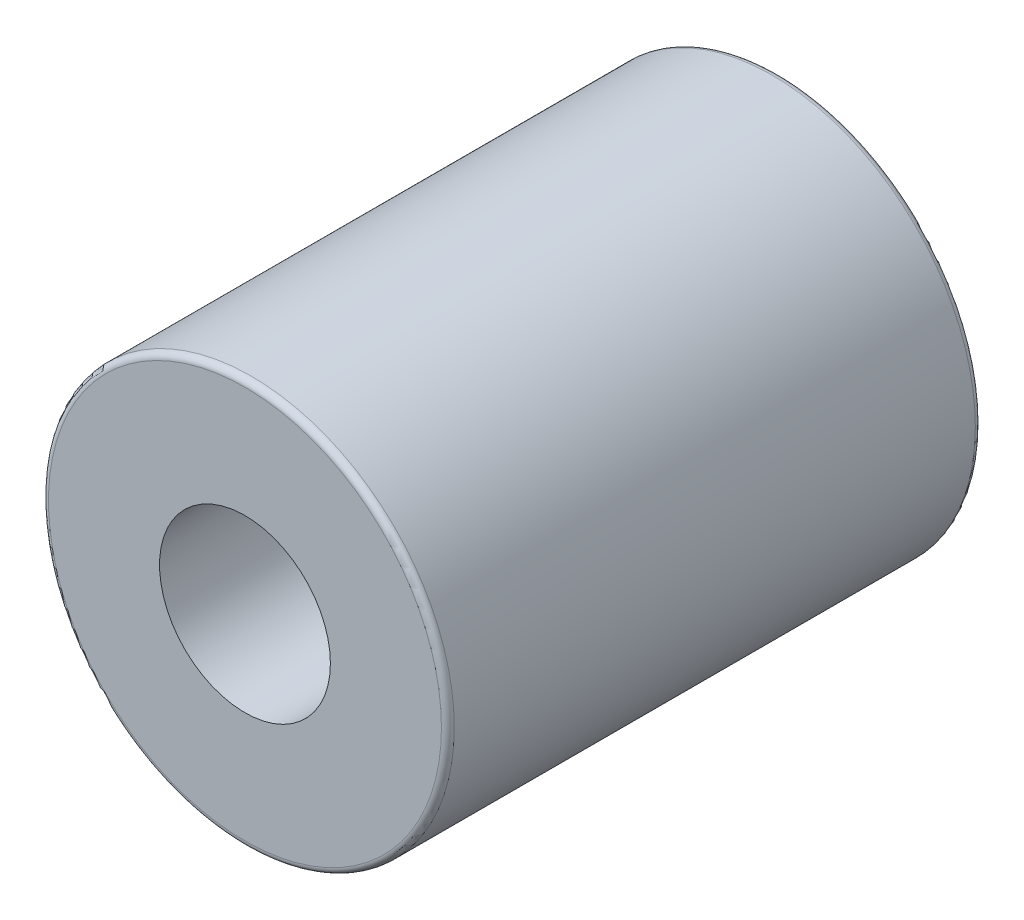
SolidWorks part; units mm, degrees
ref_plane "前视基准面" through (0, 0, 0) normal (0, 0, 1) x (1, 0, 0)
ref_plane "上视基准面" through (0, 0, 0) normal (0, 1, 0) x (1, 0, 0)
ref_plane "右视基准面" through (0, 0, 0) normal (1, 0, 0) x (0, 0, -1)
sketch "草图1" plane through (0, 0, 0) normal (0, 0, 1) x (1, 0, 0)
  circle A0 centre (0, 0) radius 2.5
  circle A1 centre (0, 0) radius 9.5
  dimension "D1" = 19
  dimension "D2" = 5
extrude "凸台-拉伸1" add sketch "草图1" along normal blind 25
sketch "草图2" plane through (0, 0, 25) normal (0, 0, 1) x (1, 0, 0)
  circle A0 centre (0, 0) radius 4
  dimension "D1" = 8
extrude "切除-拉伸1" cut sketch "草图2" against normal blind 12.5
fillet "圆角1" radius 0.3 2 edges at (9.5, 0, 0) (9.5, 0, 25)
